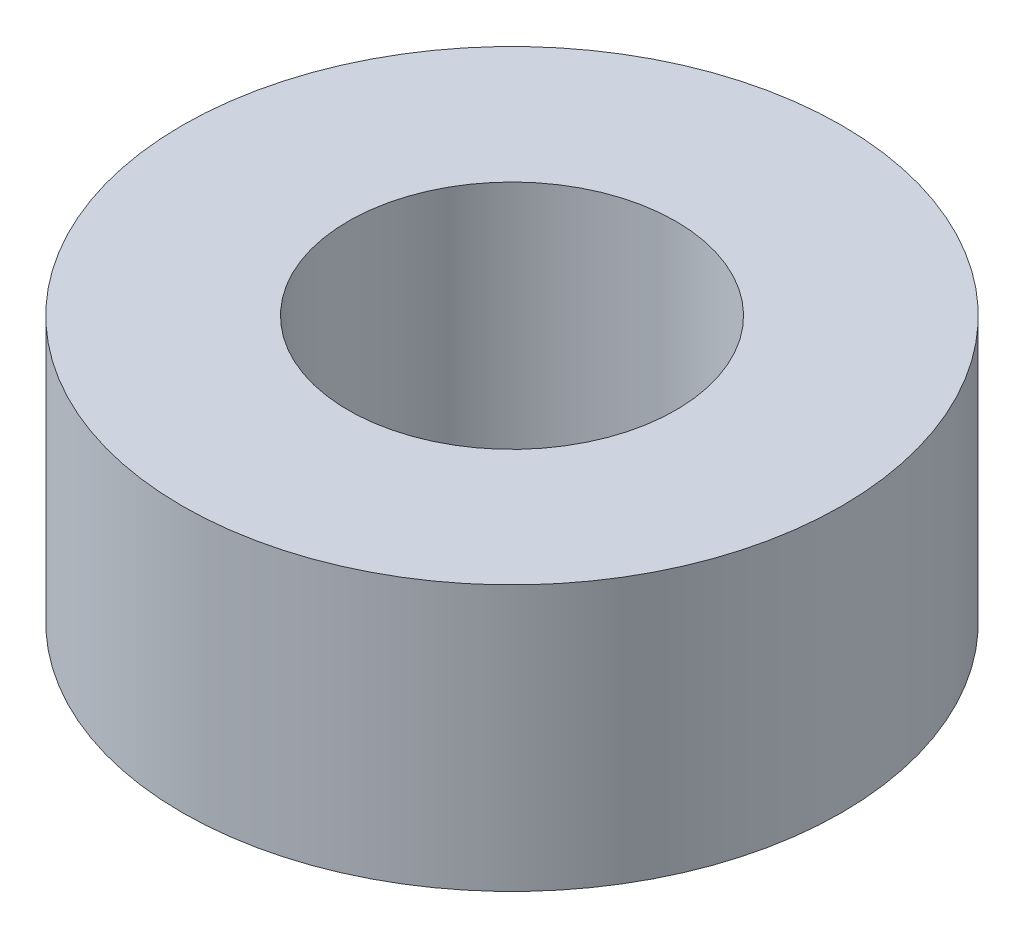
SolidWorks part; units mm, degrees
ref_plane "Front Plane" through (0, 0, 0) normal (0, 0, 1) x (1, 0, 0)
ref_plane "Top Plane" through (0, 0, 0) normal (0, 1, 0) x (1, 0, 0)
ref_plane "Right Plane" through (0, 0, 0) normal (1, 0, 0) x (0, 0, -1)
sketch "Sketch1" plane through (0, 0, 0) normal (0, 1, 0) x (1, 0, 0)
  circle A0 centre (0, 0) radius 9.4615
  circle A2 centre (0, 0) radius 4.699
  dimension "D1" = 18.923
  dimension "D2" = 9.398
extrude "Boss-Extrude1" add sketch "Sketch1" along normal blind 7.62
